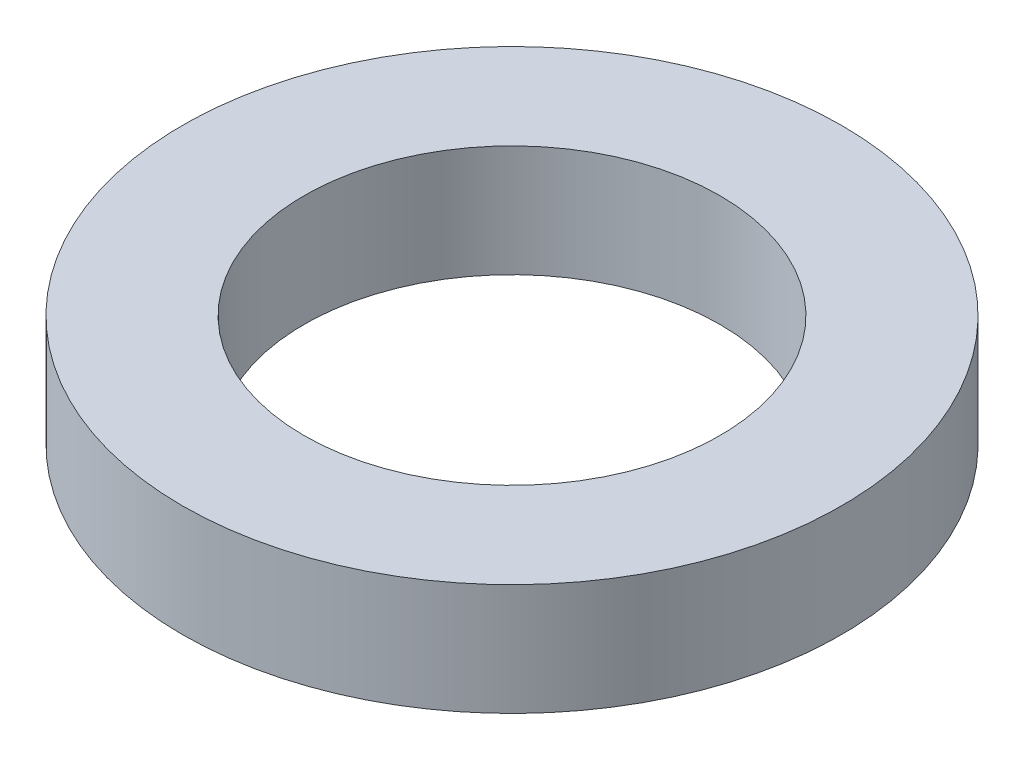
SolidWorks part; units mm, degrees
ref_plane "Спереди" through (0, 0, 0) normal (0, 0, 1) x (1, 0, 0)
ref_plane "Сверху" through (0, 0, 0) normal (0, 1, 0) x (1, 0, 0)
ref_plane "Справа" through (0, 0, 0) normal (1, 0, 0) x (0, 0, -1)
other "Configuration Table"
sketch "Sketch1" plane through (0, 0, 0) normal (0, 1, 0) x (1, 0, 0)
  circle A0 centre (0, 0) radius 2.05
  circle A1 centre (0, 0) radius 3.25
  dimension "D1" = 4.1
  dimension "D2" = 1.2
extrude "Boss-Extrude1" add sketch "Sketch1" along normal blind 1.1
